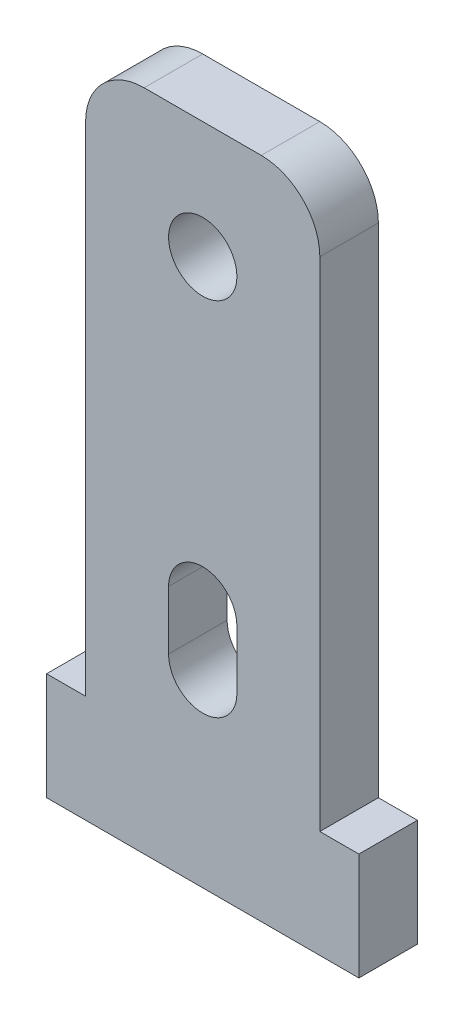
SolidWorks part; units mm, degrees
material "Custom Plastic"
ref_plane "Front Plane" through (0, 0, 0) normal (0, 0, 1) x (1, 0, 0)
ref_plane "Top Plane" through (0, 0, 0) normal (0, 1, 0) x (1, 0, 0)
ref_plane "Right Plane" through (0, 0, 0) normal (1, 0, 0) x (0, 0, -1)
sketch "Sketch1" plane through (0, 0, 0) normal (0, 0, 1) x (1, 0, 0)
  line L0 (0, -3) -> (0, -6) construction
  line L1 (-3, 18.5) -> (3, 18.5)
  line L2 (-6, 15.5) -> (-6, -15.5)
  line L3 (-6, -15.5) -> (6, -15.5)
  line L4 (6, 15.5) -> (6, -15.5)
  line L5 (-8, -10) -> (8, -10)
  line L6 (-8, -10) -> (-8, -15.5)
  line L7 (-8, -15.5) -> (8, -15.5)
  line L8 (8, -10) -> (8, -15.5)
  line L9 (1.75, -3) -> (1.75, -6)
  line L10 (-1.75, -3) -> (-1.75, -6)
  circle A0 centre (0, 12.5) radius 1.75
  arc A1 (1.75, -3) -> (-1.75, -3) centre (0, -3) ccw
  arc A2 (-1.75, -6) -> (1.75, -6) centre (0, -6) ccw
  arc A3 (3, 18.5) -> (6, 15.5) centre (3, 15.5) cw
  arc A4 (-3, 18.5) -> (-6, 15.5) centre (-3, 15.5) ccw
  point P8 (6, 0)
  point P10 (0, -15.5)
  point P11 (0, -15.5)
  point P12 (0, 18.5)
  point P17 (0, -4.5)
  point P24 (6, 18.5)
  point P27 (-6, 18.5)
  dimension "D5" = 3.5
  dimension "D6" = 1.75
  dimension "D10" = 3
  dimension "D1" = 34
  dimension "D2" = 5.5
  dimension "D3" = 12
  dimension "D4" = 16
  dimension "D7" = 17
  dimension "D8" = 4
  dimension "D9" = 3
extrude "Boss-Extrude1" add sketch "Sketch1" along normal blind 3 contours L2 L5 L4 L1 A2 L10 A1 L9 A0 | L5 L2 L3 L4 | L6 L7 L2 L5 | L8 L5 L4 L7
